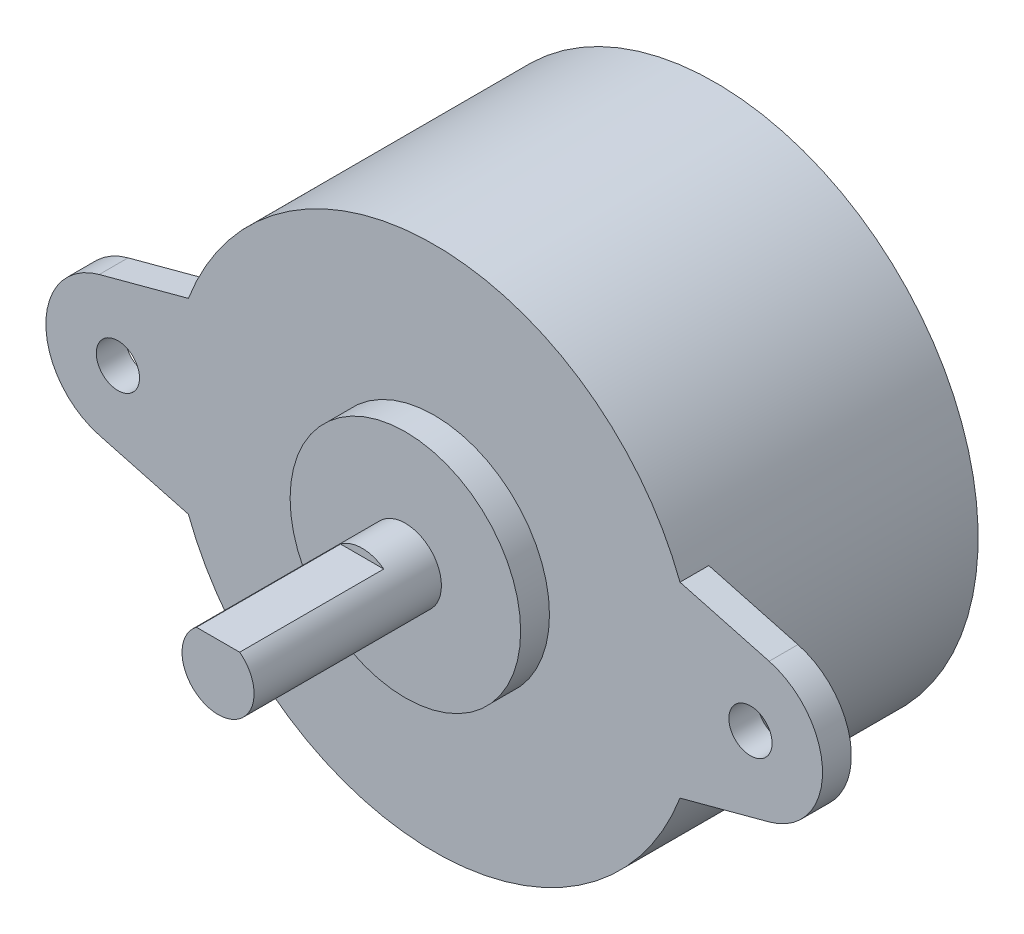
SolidWorks part; units mm, degrees
material "Plain Carbon Steel"
ref_plane "Front Plane" through (0, 0, 0) normal (0, 0, 1) x (1, 0, 0)
ref_plane "Top Plane" through (0, 0, 0) normal (0, 1, 0) x (1, 0, 0)
ref_plane "Right Plane" through (0, 0, 0) normal (1, 0, 0) x (0, 0, -1)
sketch "Sketch1" plane through (0, 0, 0) normal (0, 0, 1) x (1, 0, 0)
  line L0 (-21.95, 0) -> (21.95, 0) construction
  line L1 (-23.2441, 4.8296) -> (-17.0581, 6.4872)
  line L2 (-23.2441, -4.8296) -> (-17.0581, -6.4872)
  line L3 (23.2441, 4.8296) -> (17.0581, 6.4872)
  line L4 (23.2441, -4.8296) -> (17.0581, -6.4872)
  arc A0 (-17.0581, -6.4872) -> (17.0581, -6.4872) centre (0, 0) ccw
  circle A1 centre (-21.95, 0) radius 1.5
  circle A2 centre (21.95, 0) radius 1.5
  arc A3 (23.2441, -4.8296) -> (23.2441, 4.8296) centre (21.95, 0) ccw
  arc A4 (-23.2441, 4.8296) -> (-23.2441, -4.8296) centre (-21.95, 0) ccw
  arc A5 (17.0581, 6.4872) -> (-17.0581, 6.4872) centre (0, 0) ccw
  dimension "D1" = 36.5
  dimension "D3" = 3
  dimension "D4" = 3
  dimension "D5" = 10
  dimension "D6" = 10
  dimension "D2" = 43.9
  dimension "D7" = 15
  dimension "D8" = 15
  dimension "D9" = 15
  dimension "D10" = 15
extrude "Boss-Extrude1" add sketch "Sketch1" against normal blind 2
sketch "Sketch2" plane through (0, 0, -2) normal (0, 0, -1) x (-1, 0, 0)
  circle A0 centre (0, 0) radius 18.25
extrude "Boss-Extrude2" add sketch "Sketch2" along normal blind 17.5
sketch "Sketch3" plane through (0, 0, 0) normal (0, 0, 1) x (1, 0, 0)
  circle A0 centre (0, 0) radius 8
  dimension "D1" = 16
extrude "Boss-Extrude3" add sketch "Sketch3" along normal blind 2
sketch "Sketch4" plane through (0, 0, 2) normal (0, 0, 1) x (1, 0, 0)
  circle A0 centre (0, 0) radius 2.5
  dimension "D1" = 5
extrude "Boss-Extrude4" add sketch "Sketch4" along normal blind 13
sketch "Sketch5" plane through (0, 0, 15) normal (0, 0, 1) x (1, 0, 0)
  line L0 (1.5, 2) -> (-1.5, 2)
  circle A0 centre (0, 0) radius 2.5 construction
  circle A1 centre (0, 0) radius 2.5 construction
  arc A2 (1.5, 2) -> (-1.5, 2) centre (0, 0) ccw
  dimension "D1" = 4.5
extrude "Cut-Extrude1" cut sketch "Sketch5" against normal blind 10
